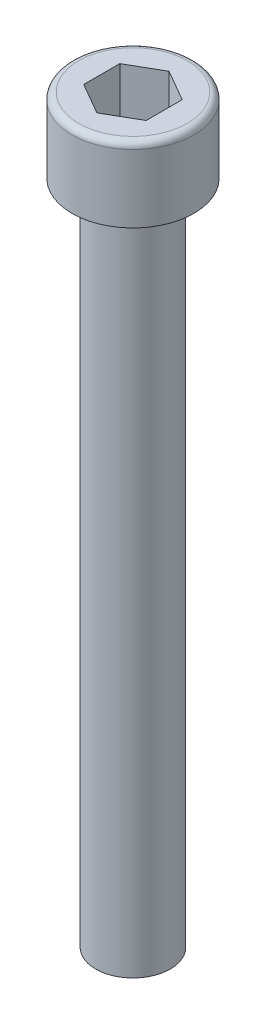
SolidWorks part; units mm, degrees
ref_plane "Front Plane" through (0, 0, 0) normal (0, 0, 1) x (1, 0, 0)
ref_plane "Top Plane" through (0, 0, 0) normal (0, 1, 0) x (1, 0, 0)
ref_plane "Right Plane" through (0, 0, 0) normal (1, 0, 0) x (0, 0, -1)
sketch "Sketch1" plane through (0, 0, 0) normal (0, 1, 0) x (1, 0, 0)
  circle A0 centre (0, 0) radius 1.4224
  dimension "D1" = 2.8448
extrude "Shaft" add sketch "Sketch1" against normal blind 25.4
sketch "Sketch2" plane through (0, 0, 0) normal (0, 1, 0) x (1, 0, 0)
  circle A0 centre (0, 0) radius 2.3241
  dimension "D1" = 4.6482
extrude "Head" add sketch "Sketch2" along normal blind 2.8448
fillet "Fillet1" radius 0.254 1 edges at (0, 2.8448, 2.3241)
sketch "Sketch3" plane through (0, 2.8448, 0) normal (0, 1, 0) x (1, 0, 0)
  line L1 (0, 1.3748) -> (-1.1906, 0.6874)
  line L2 (-1.1906, 0.6874) -> (-1.1906, -0.6874)
  line L3 (-1.1906, -0.6874) -> (0, -1.3748)
  line L4 (0, -1.3748) -> (1.1906, -0.6874)
  line L5 (1.1906, -0.6874) -> (1.1906, 0.6874)
  line L6 (1.1906, 0.6874) -> (0, 1.3748)
  circle A0 centre (0, 0) radius 1.1906 construction
  dimension "D1" = 2.3813
extrude "Hex" cut sketch "Sketch3" against normal blind 1.905
